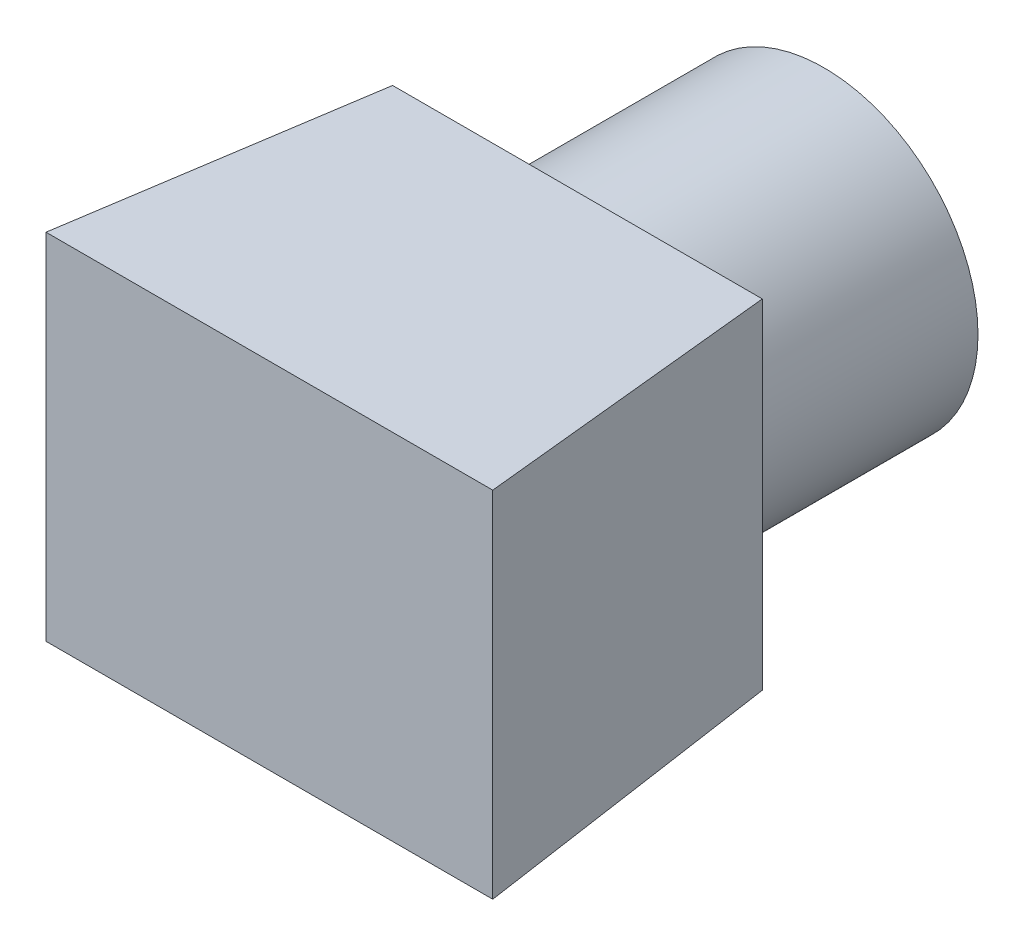
SolidWorks part; units mm, degrees
ref_plane "Front Plane" through (0, 0, 0) normal (0, 0, 1) x (1, 0, 0)
ref_plane "Top Plane" through (0, 0, 0) normal (0, 1, 0) x (1, 0, 0)
ref_plane "Right Plane" through (0, 0, 0) normal (1, 0, 0) x (0, 0, -1)
sketch "Sketch1" plane through (0, 0, 0) normal (0, 0, 1) x (1, 0, 0)
  circle A0 centre (0, 0) radius 5
  dimension "10" = 10
extrude "Boss-Extrude1" add sketch "Sketch1" along normal blind 8
sketch "Sketch2" plane through (0, 0, 8) normal (0, 0, 1) x (1, 0, 0)
  line L1 (6, -5.5) -> (-6, -5.5)
  line L2 (6, -5.5) -> (6, 5.5)
  line L3 (6, 5.5) -> (-6, 5.5)
  line L4 (-6, -5.5) -> (-6, 5.5)
  line L5 (6, -5.5) -> (-6, 5.5) construction
  line L6 (6, 5.5) -> (-6, -5.5) construction
  point P0 (0, 0)
  dimension "D1" = 11
  dimension "D2" = 12
extrude "Boss-Extrude2" add sketch "Sketch2" along normal blind 10
sketch "Sketch3" plane through (0, 0, 8) normal (0, 0, -1) x (-1, 0, 0)
  line L4 (6, -5.5) -> (6, 5.5)
  line L5 (6, 5.5) -> (-6, 5.5)
  line L6 (-6, 5.5) -> (-6, -5.5)
  line L7 (-6, -5.5) -> (6, -5.5)
  line L8 (6, -5.5) -> (6, 5.5)
  line L9 (6, 5.5) -> (-6, 5.5)
  line L10 (-6, 5.5) -> (-6, -5.5)
  line L11 (-6, -5.5) -> (6, -5.5)
  dimension "D1" = 0
sketch "Sketch4" plane through (0, 0, 18) normal (0, 0, 1) x (1, 0, 0)
  line L1 (7.25, -5.75) -> (-7.25, -5.75)
  line L2 (7.25, -5.75) -> (7.25, 5.75)
  line L3 (7.25, 5.75) -> (-7.25, 5.75)
  line L4 (-7.25, -5.75) -> (-7.25, 5.75)
  line L5 (7.25, -5.75) -> (-7.25, 5.75) construction
  line L6 (7.25, 5.75) -> (-7.25, -5.75) construction
  point P0 (0, 0)
  dimension "D1" = 14.5
  dimension "D2" = 11.5
loft "Loft1" add profiles "Sketch3", "Sketch4"
